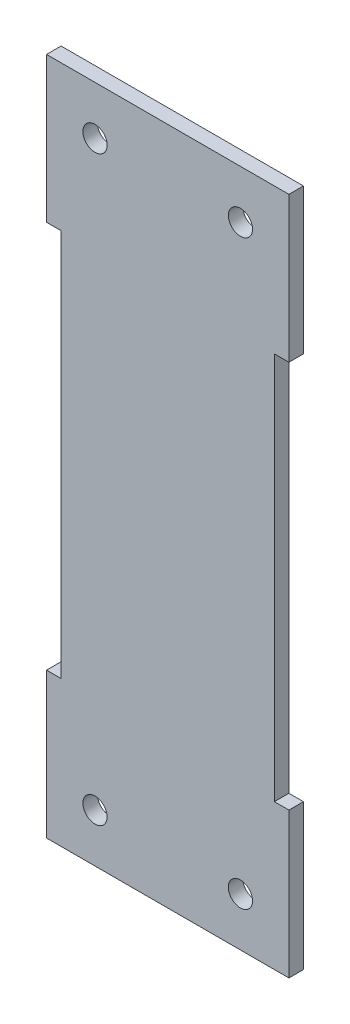
SolidWorks part; units mm, degrees
ref_plane "Front Plane" through (0, 0, 0) normal (0, 0, 1) x (1, 0, 0)
ref_plane "Top Plane" through (0, 0, 0) normal (0, 1, 0) x (1, 0, 0)
ref_plane "Right Plane" through (0, 0, 0) normal (1, 0, 0) x (0, 0, -1)
sketch "Sketch1" plane through (0, 0, 0) normal (0, 0, 1) x (1, 0, 0)
  line L0 (25, 0) -> (-25, 0) construction
  line L1 (25, -70) -> (-25, -70)
  line L2 (25, -70) -> (25, -40)
  line L3 (25, 70) -> (-25, 70)
  line L4 (-25, -70) -> (-25, -40)
  line L5 (25, -70) -> (-25, 70) construction
  line L6 (25, 70) -> (-25, -70) construction
  line L7 (-25, 40) -> (-22, 40)
  line L8 (-22, 40) -> (-22, -40)
  line L9 (-22, -40) -> (-25, -40)
  line L10 (25, 40) -> (22, 40)
  line L11 (22, 40) -> (22, -40)
  line L12 (22, -40) -> (25, -40)
  line L13 (-25, 40) -> (-25, 70)
  line L14 (25, 40) -> (25, 70)
  circle A0 centre (-15, 60) radius 2.5
  circle A1 centre (15, 60) radius 2.5
  circle A2 centre (15, -60) radius 2.5
  circle A3 centre (-15, -60) radius 2.5
  point P0 (0, 0)
  dimension "D3" = 5
  dimension "5" = 5
  dimension "D1" = 50
  dimension "D2" = 140
  dimension "D4" = 30
  dimension "D5" = 10
  dimension "D6" = 10
  dimension "D7" = 10
  dimension "D8" = 80
  dimension "D9" = 30
  dimension "D10" = 3
  dimension "D11" = 80
  dimension "D12" = 30
  dimension "D13" = 3
  dimension "D14" = 3
extrude "Boss-Extrude1" add sketch "Sketch1" along normal blind 3
